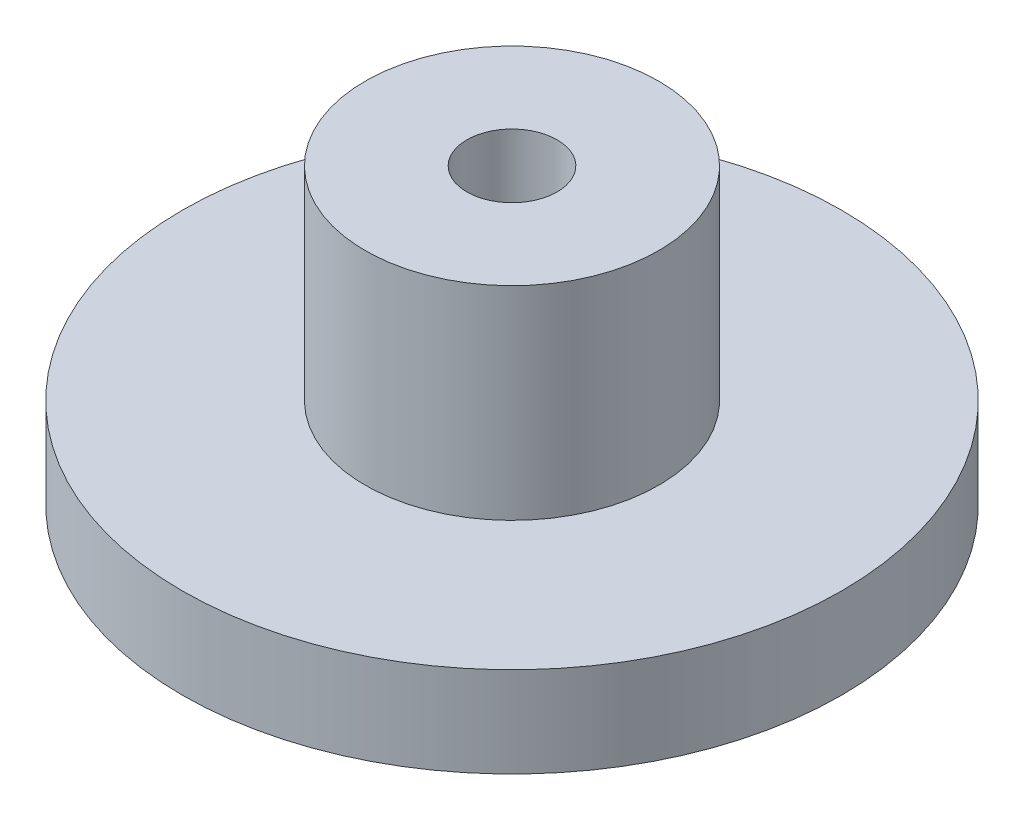
SolidWorks part; units mm, degrees
material "Nylon 101"
ref_plane "Front Plane" through (0, 0, 0) normal (0, 0, 1) x (1, 0, 0)
ref_plane "Top Plane" through (0, 0, 0) normal (0, 1, 0) x (1, 0, 0)
ref_plane "Right Plane" through (0, 0, 0) normal (1, 0, 0) x (0, 0, -1)
sketch "Sketch1" plane through (0, 0, 0) normal (0, 0, 1) x (1, 0, 0)
  line L0 (0, 0) -> (0, 6.5) construction
  line L1 (1, 6.5) -> (1, 0)
  line L2 (1, 0) -> (2.5, 0)
  line L3 (2.5, 0) -> (2.5, 0.6)
  line L4 (2.5, 0.6) -> (5.5, 0.6)
  line L5 (5.5, 0.6) -> (5.5, 0)
  line L6 (5.5, 0) -> (7.3, 0)
  line L7 (7.3, 0) -> (7.3, 2)
  line L8 (7.3, 2) -> (3.25, 2)
  line L11 (3.25, 2) -> (3.25, 6.5)
  line L12 (3.25, 6.5) -> (1, 6.5)
  line L13 (0, 6.5) -> (1, 6.5) construction
  line L14 (0, 0) -> (1, 0) construction
  dimension "D1" = 2
  dimension "D2" = 5
  dimension "D3" = 11
  dimension "D4" = 14.6
  dimension "D5" = 6.5
  dimension "D6" = 0.6
  dimension "D8" = 2
  dimension "D9" = 6.5
revolve "14 and 35" add sketch "Sketch1" angle 360 about L0
